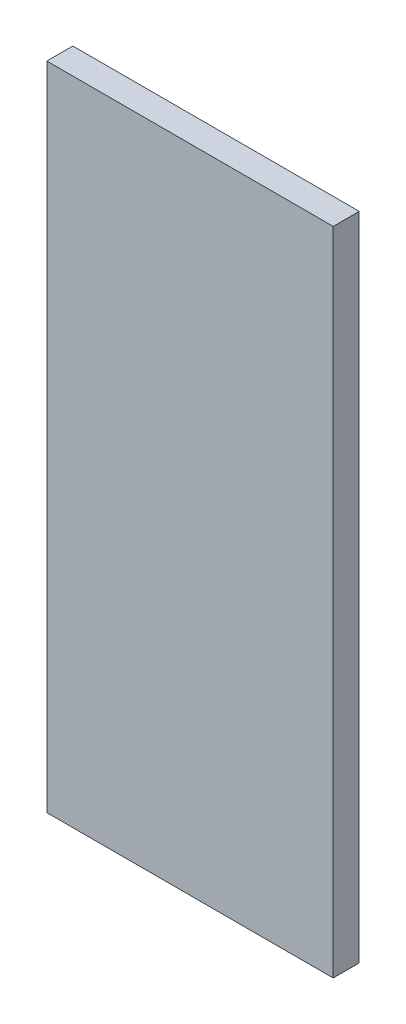
SolidWorks part; units mm, degrees
ref_plane "Front" through (0, 0, 0) normal (0, 0, 1) x (1, 0, 0)
ref_plane "Top" through (0, 0, 0) normal (0, 1, 0) x (1, 0, 0)
ref_plane "Right" through (0, 0, 0) normal (1, 0, 0) x (0, 0, -1)
sketch "Sketch1" plane through (0, 0, 0) normal (0, 0, 1) x (1, 0, 0)
  line L0 (-9.174, -20.1218) -> (-9.174, 29.8782)
  line L1 (-9.174, 29.8782) -> (12.826, 29.8782)
  line L2 (12.826, -20.1218) -> (-9.174, -20.1218)
  line L3 (12.826, 29.8782) -> (12.826, -20.1218)
  dimension "D1" = 22
  dimension "D2" = 50
extrude "Boss-Extrude1" add sketch "Sketch1" along normal blind 2
